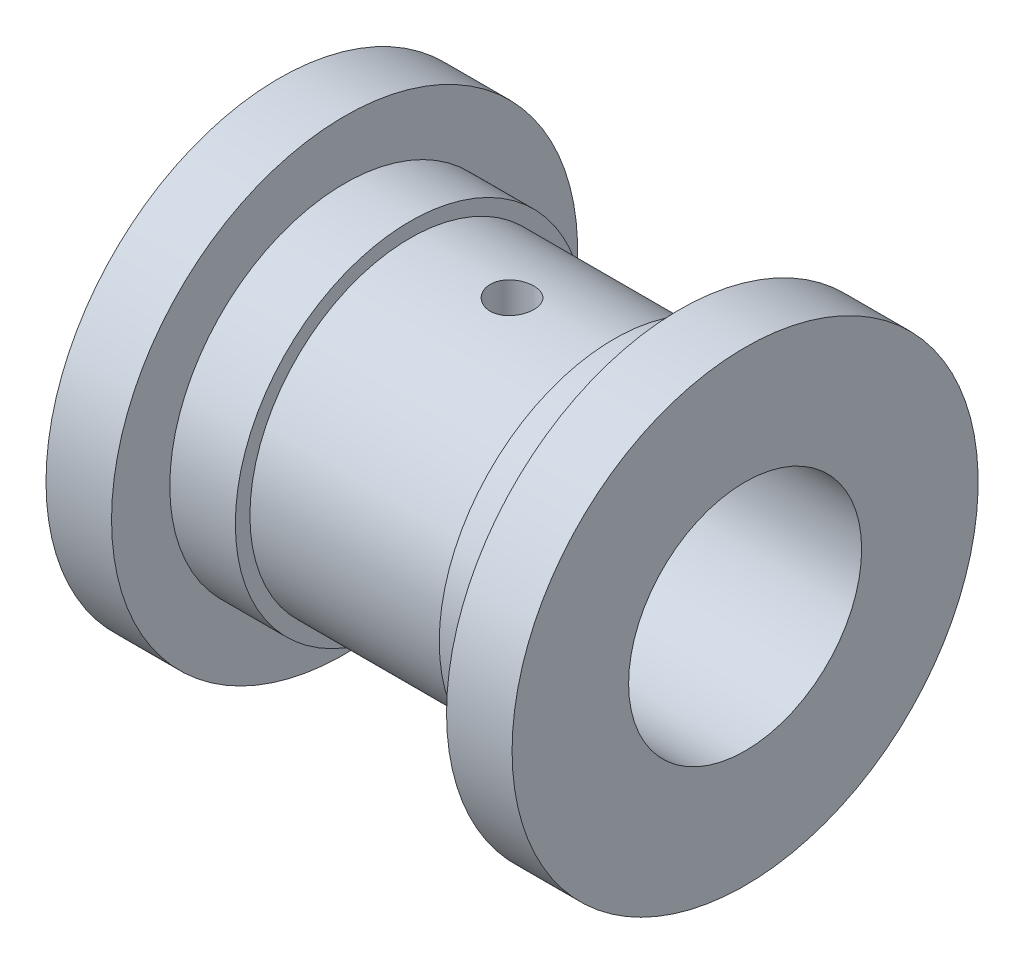
SolidWorks part; units mm, degrees
material "Brass"
ref_plane "Front Plane" through (0, 0, 0) normal (0, 0, 1) x (1, 0, 0)
ref_plane "Top Plane" through (0, 0, 0) normal (0, 1, 0) x (1, 0, 0)
ref_plane "Right Plane" through (0, 0, 0) normal (1, 0, 0) x (0, 0, -1)
sketch "Sketch1" plane through (0, 0, 0) normal (0, 0, 1) x (1, 0, 0)
  line L0 (0, -0.9024) -> (0, -98815.5636) construction
  line L1 (0, 0) -> (98814.6613, 0) construction
  line L2 (-32, 16) -> (32, 16)
  line L3 (32, 16) -> (32, 32)
  line L4 (32, 32) -> (23, 32)
  line L5 (23, 32) -> (23, 24)
  line L6 (23, 24) -> (14, 24)
  line L7 (14, 24) -> (14, 22)
  line L8 (-14, 24) -> (-14, 22)
  line L9 (-23, 24) -> (-14, 24)
  line L10 (-23, 32) -> (-23, 24)
  line L11 (-32, 32) -> (-23, 32)
  line L12 (-32, 16) -> (-32, 32)
  line L13 (-14, 22) -> (14, 22)
  point P8 (0, 16)
  dimension "D1" = 28
  dimension "D2" = 46
  dimension "D3" = 9
  dimension "D4" = 32
  dimension "D5" = 48
  dimension "D6" = 44
  dimension "D7" = 64
revolve "Revolve1" add sketch "Sketch1" angle 360 about L1
ref_plane "Plane1" through (0, -30, 0) normal (0, 1, 0) x (1, 0, 0)
sketch "Sketch2" plane through (0, -30, 0) normal (0, 1, 0) x (1, 0, 0)
  circle A0 centre (0, 0) radius 4
  dimension "D1" = 8
extrude "Boss-Extrude1" add sketch "Sketch2" along normal up to next
hole_wizard "Ø1.0mm Dowel Hole1" positions "Sketch3" profile "Sketch4" hole size "Ø1.0" standard "ANSI Metric" end condition through all
sketch "Sketch3" plane through (0, -30, 0) normal (0, -1, 0) x (-1, 0, 0)
  point P0 (0, 0)
sketch "Sketch4" plane through (0, -30, 0) normal (1, 0, 0) x (0, 0, -1)
  line L0 (0, 0) -> (0, 62)
  line L1 (0, 62) -> (3, 62)
  line L2 (3, 62) -> (3, 0)
  line L5 (3, 0) -> (0, 0)
  line L11 (0, -6.35) -> (0, 107.95) construction
  dimension "Thru Hole Dia." = 6
  dimension "Thru Hole Depth" = 62
